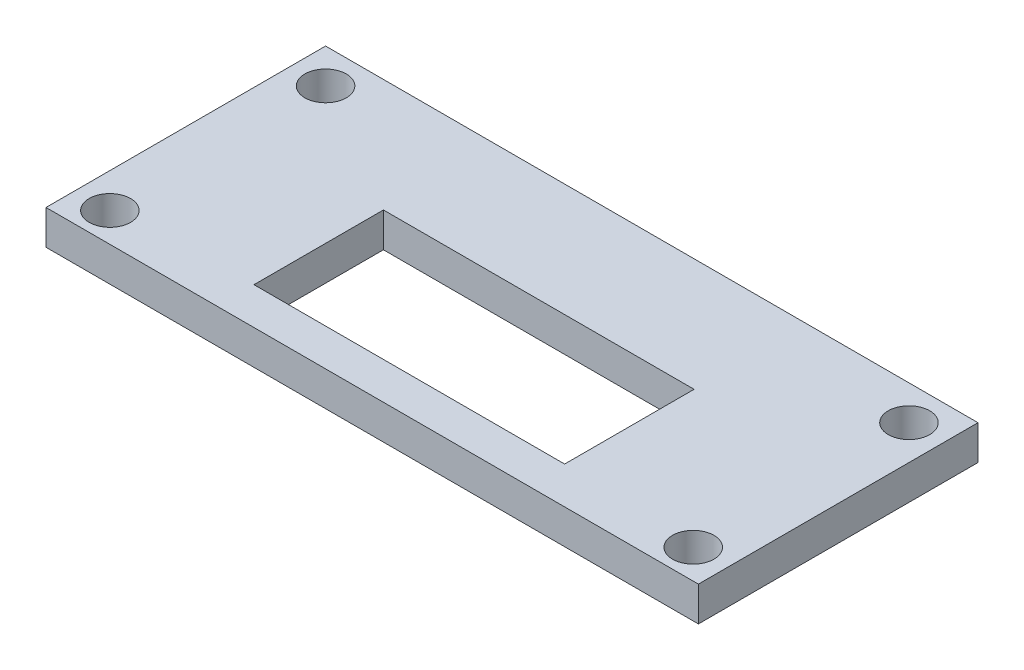
SolidWorks part; units mm, degrees
ref_plane "Front Plane" through (0, 0, 0) normal (0, 0, 1) x (1, 0, 0)
ref_plane "Top Plane" through (0, 0, 0) normal (0, 1, 0) x (1, 0, 0)
ref_plane "Right Plane" through (0, 0, 0) normal (1, 0, 0) x (0, 0, -1)
ref_plane "PZ15" through (0, 15, 0) normal (0, 1, 0) x (1, 0, 0)
sketch "Sketch1" plane through (0, 15, 0) normal (0, 1, 0) x (1, 0, 0)
  line L0 (-18.9, 29.3) -> (18.9, 29.3)
  line L1 (18.9, 29.3) -> (18.9, 45.5)
  line L2 (18.9, 45.5) -> (-18.9, 45.5)
  line L3 (-18.9, 45.5) -> (-18.9, 29.3)
extrude "Retainer Plate" add sketch "Sketch1" along normal blind 2
ref_plane "PZ14" through (0, 14, 0) normal (0, 1, 0) x (1, 0, 0)
sketch "Sketch2" plane through (0, 14, 0) normal (0, 1, 0) x (1, 0, 0)
  line L0 (-9, 31.45) -> (9, 31.45)
  line L1 (9, 31.45) -> (9, 38.95)
  line L2 (9, 38.95) -> (-9, 38.95)
  line L3 (-9, 38.95) -> (-9, 31.45)
extrude "Ribbon Slot" cut sketch "Sketch2" along normal blind 4
sketch "Sketch3" plane through (0, 14, 0) normal (0, 1, 0) x (1, 0, 0)
  circle A0 centre (-16.9, 31) radius 1.2
  circle A1 centre (-16.9, 43.5) radius 1.2
  circle A2 centre (16.9, 31) radius 1.2
  circle A3 centre (16.9, 43.5) radius 1.2
extrude "M2 Clearance Holes" cut sketch "Sketch3" along normal blind 4
equation "\"BOARD_REAR\" = 86.0"
equation "\"BOARD_FRONT\" = 41.0"
equation "\"BOARD_END\" = 22.0"
equation "\"BOARD_ANGLED\" = 30.0"
equation "\"BOARD_DEPTH\" = 41.8431"
equation "\"PCB_T\" = 1.6"
equation "\"ABOVE_PCB\" = 14.0"
equation "\"BELOW_PCB\" = 6.0"
equation "\"MID_PARTS_H\" = 9.0"
equation "\"BOARD_HOLE_PILOT\" = 1.6"
equation "\"J2_X\" = 19.0"
equation "\"DUPONT_DROP\" = 14.0"
equation "\"BEND_R\" = 5.0"
equation "\"BOARD_GAP\" = 3.0"
equation "\"TOF_FOV\" = 25.0"
equation "\"TOF_MARGIN_DEG\" = 5.0"
equation "\"TOF_WIN_MARGIN\" = 1.0"
equation "\"TOF_Z\" = 9.0"
equation "\"TOF_SIDE_BEARING\" = 90.0"
equation "\"TOF_CONE_LEN\" = 70.0"
equation "\"CAM_W\" = 29.2"
equation "\"CAM_H\" = 28.2"
equation "\"CAM_D\" = 12.35"
equation "\"CAM_FRONT_Y\" = 43.0"
equation "\"CAM_BOTTOM_Z\" = 17.0"
equation "\"CAM_LENS_UP\" = 11.6"
equation "\"CAM_LENS_OPEN\" = 9.6"
equation "\"CAM_HFOV\" = 53.5"
equation "\"CAM_VFOV\" = 41.41"
equation "\"CAM_FOV_MARGIN\" = 3.0"
equation "\"CAM_FIT\" = 0.3"
equation "\"RIBBON_W\" = 16.0"
equation "\"RIBBON_T\" = 0.3"
equation "\"RIBBON_LEN\" = 150.0"
equation "\"RIBBON_EXIT_Y\" = 35.0"
equation "\"WALL\" = 2.4"
equation "\"HEAD_X\" = 48.4"
equation "\"HEAD_REAR_Y\" = -11.9"
equation "\"CAM_FOAM\" = 2.8"
equation "\"HEAD_FRONT_Y\" = 48.2"
equation "\"HEAD_TOP_Z\" = 50.6"
equation "\"HEAD_BOT_Z\" = -28.4"
equation "\"HEAD_SPLIT_Z\" = -4.0"
equation "\"SKIRT_T\" = 1.2"
equation "\"SKIRT_H\" = 3.0"
equation "\"SKIRT_FIT\" = 0.3"
equation "\"VISOR\" = 7.8"
equation "\"VISOR_Z\" = 40.0"
equation "\"ROOF_SLOPE_Y\" = 40.0"
equation "\"ROOF_CHAMFER\" = 10.0"
equation "\"REAR_CHAMFER\" = 10.0"
equation "\"CORNER_CHAMFER\" = 6.0"
equation "\"LOWER_SIDE_FACET\" = 6.0"
equation "\"LIGHTBAR_DEPTH\" = 1.0"
equation "\"HOOD_Z\" = 14.0"
equation "\"HOOD_L\" = 6.0"
equation "\"SIDE_HOOD_L\" = 4.0"
equation "\"INSERT_M3_D\" = 4.0"
equation "\"INSERT_M3_L\" = 6.0"
equation "\"M3_CLEAR\" = 3.4"
equation "\"M2_PILOT\" = 1.6"
equation "\"M25_PILOT\" = 2.2"
equation "\"BOX_X\" = 72.4"
equation "\"BOX_FRONT_Y\" = -11.9"
equation "\"BOX_REAR_Y\" = -154.4"
equation "\"BOX_BOT_Z\" = -28.4"
equation "\"BOX_TOP_Z\" = 10.0"
equation "\"LID_T\" = 2.4"
equation "\"LID_SKIRT\" = 1.6"
equation "\"LID_TONGUE_H\" = 3.0"
equation "\"LID_FIT\" = 0.3"
equation "\"GNSS_WIN_T\" = 1.2"
equation "\"DIVIDER_Y\" = -86.0"
equation "\"PI_X0\" = -40.0"
equation "\"PI_X1\" = 45.0"
equation "\"PI_Y1\" = -26.3"
equation "\"PI_Y0\" = -82.3"
equation "\"PI_STANDOFF\" = 8.0"
equation "\"ESP_X0\" = -46.0"
equation "\"ESP_Y0\" = -149.0"
equation "\"ESP_L\" = 75.0"
equation "\"ESP_W\" = 52.0"
equation "\"ESP_STANDOFF\" = 12.0"
equation "\"VENT_UPSTAND\" = 3.0"
equation "\"TUBE_D\" = 22.2"
equation "\"TUBE_LINER\" = 1.0"
equation "\"MOUNT_Y\" = -70.0"
equation "\"RAIL_W\" = 30.0"
equation "\"RAIL_W2\" = 38.0"
equation "\"RAIL_H\" = 6.0"
equation "\"SLIDE\" = 0.3"
equation "\"STOP_T\" = 6.0"
equation "\"CLAMP_W\" = 40.0"
equation "\"CLAMP_HALF\" = 20.0"
equation "\"CLAMP_DROP\" = 12.0"
equation "\"CAP_T\" = 12.0"
equation "\"CLAMP_BOLT_OFF\" = 16.6"
equation "\"M5_INSERT_D\" = 6.4"
equation "\"M5_CLEAR\" = 5.5"
equation "\"LOCK_D\" = 3.3"
equation "\"POD_TILT_DEG\" = 0.0"
equation "\"PRINT_LIMIT\" = 180.0"
